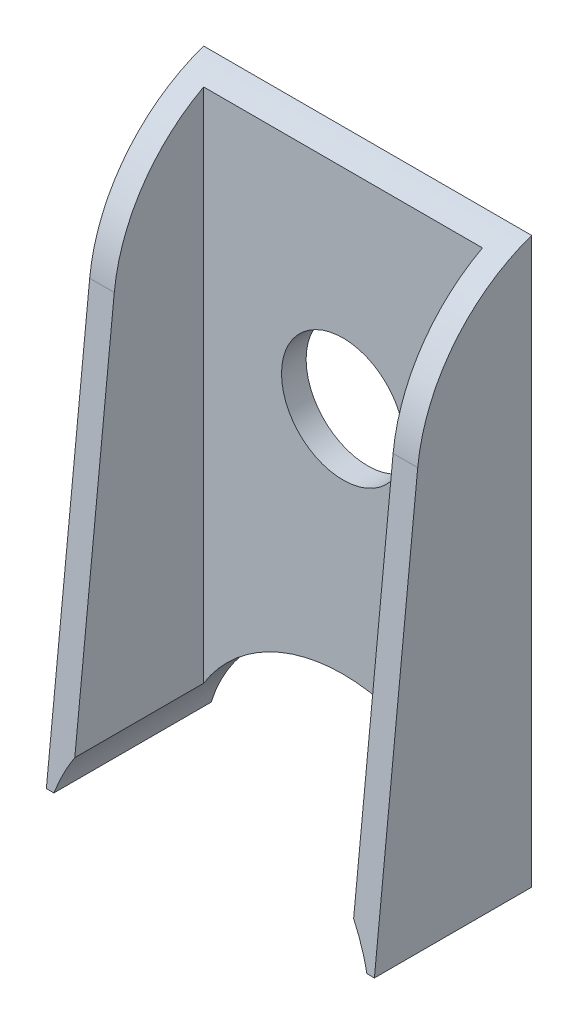
SolidWorks part; units mm, degrees
ref_plane "Front Plane" through (0, 0, 0) normal (0, 0, 1) x (1, 0, 0)
ref_plane "Top Plane" through (0, 0, 0) normal (0, 1, 0) x (1, 0, 0)
ref_plane "Right Plane" through (0, 0, 0) normal (1, 0, 0) x (0, 0, -1)
sketch "Sketch1" plane through (0, 0, 0) normal (0, 1, 0) x (1, 0, 0)
  line L0 (-12.7, -12.7) -> (-10.795, -12.7)
  line L1 (-10.795, -12.7) -> (-10.795, -1.905)
  line L2 (-10.795, -1.905) -> (10.795, -1.905)
  line L3 (10.795, -1.905) -> (10.795, -12.7)
  line L4 (10.795, -12.7) -> (12.7, -12.7)
  line L5 (12.7, -12.7) -> (12.7, 0)
  line L6 (12.7, 0) -> (-12.7, 0)
  line L7 (-12.7, 0) -> (-12.7, -12.7)
  point P8 (0, 0)
  dimension "D1" = 1.905
  dimension "D2" = 25.4
  dimension "D3" = 12.7
  dimension "D4" = 1.905
extrude "Boss-Extrude1" add sketch "Sketch1" along normal blind 49.53
sketch "Sketch2" plane through (12.7, 0, 0) normal (1, 0, 0) x (0, 0, -1)
  line L0 (-12.7, 0) -> (-8.8219, 37.6239)
  line L1 (-12.7, 0) -> (-12.7, 49.53)
  line L2 (-12.7, 49.53) -> (4.3744, 49.53)
  line L3 (-12.7, 49.53) -> (0, 49.53) construction
  arc A0 (-8.8219, 37.6239) -> (4.3744, 49.53) centre (4.3744, 36.2637) cw
extrude "Cut-Extrude1" cut sketch "Sketch2" against normal blind 44.45
sketch "Sketch3" plane through (0, 0, 0) normal (0, 0, -1) x (-1, 0, 0)
  line L0 (-12.7, 44.45) -> (12.7, 44.45) construction
  line L1 (-12.115, 5.08) -> (-12.7, 5.08)
  line L2 (-12.7, 48.788) -> (-12.7, 0) construction
  line L3 (12.115, 5.08) -> (12.7, 5.08)
  line L4 (12.7, 48.788) -> (12.7, 0) construction
  line L5 (-12.7, 5.08) -> (-12.7, 0)
  line L6 (-12.7, 0) -> (12.7, 0)
  line L7 (12.7, 0) -> (12.7, 5.08)
  circle A0 centre (0, 31.75) radius 4.7625
  arc A1 (12.115, 5.08) -> (-12.115, 5.08) centre (0, 1.27) ccw
  point P18 (0.8032, 0.9837)
  dimension "D2" = 9.525
  dimension "D3" = 25.4
  dimension "D1" = 12.7
  dimension "D4" = 1.27
  dimension "D5" = 5.08
extrude "Cut-Extrude2" cut sketch "Sketch3" against normal blind 44.45
